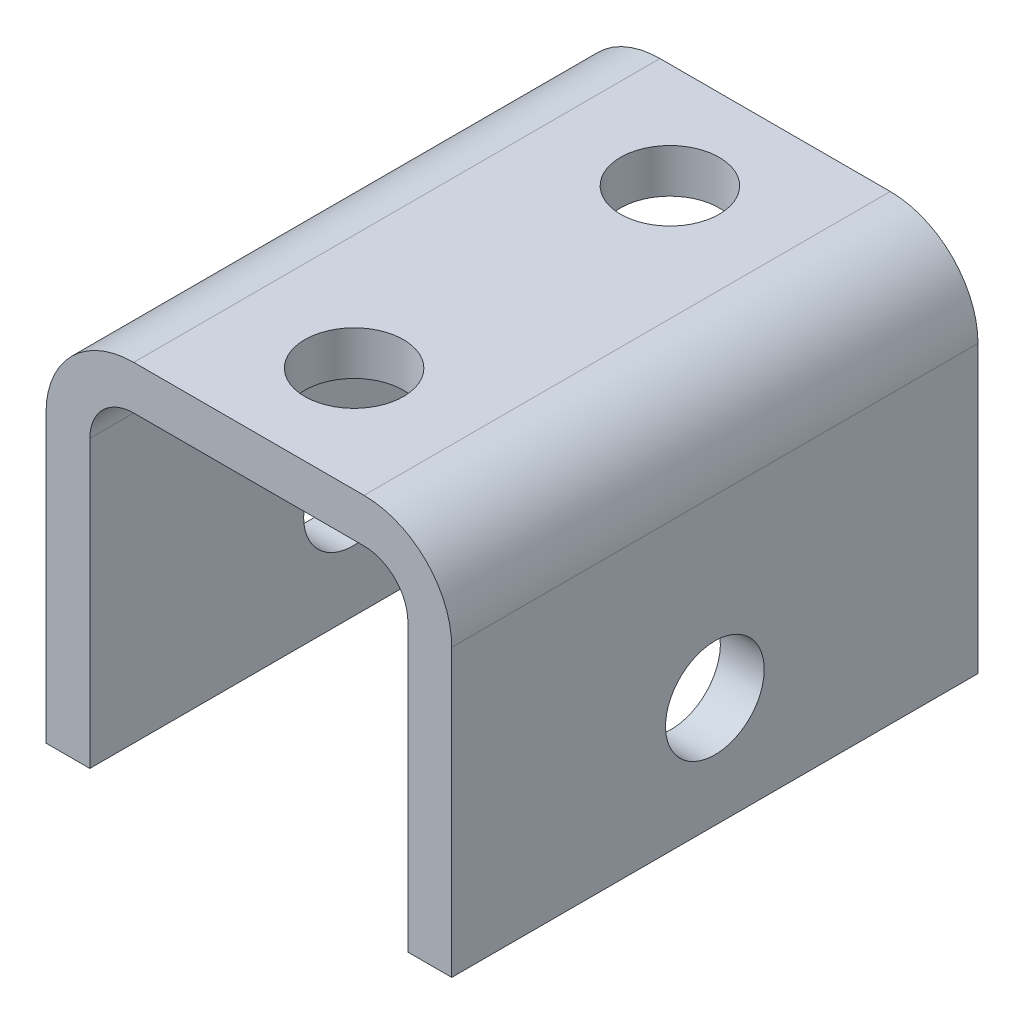
SolidWorks part; units mm, degrees
material "Plain Carbon Steel"
ref_plane "Front Plane" through (0, 0, 0) normal (0, 0, 1) x (1, 0, 0)
ref_plane "Top Plane" through (0, 0, 0) normal (0, 1, 0) x (1, 0, 0)
ref_plane "Right Plane" through (0, 0, 0) normal (1, 0, 0) x (0, 0, -1)
sketch "Sketch1" plane through (0, 0, 0) normal (0, 0, 1) x (1, 0, 0)
  line L0 (-23.0251, -12.7) -> (-23.0251, -54.102)
  line L1 (-16.6751, 0) -> (16.6751, 0)
  line L2 (-29.3751, -12.7) -> (-29.3751, -54.102)
  line L4 (29.3751, -12.7) -> (29.3751, -54.102)
  line L5 (-29.3751, 0) -> (29.3751, -54.102) construction
  line L6 (-29.3751, -54.102) -> (29.3751, 0) construction
  line L7 (-16.6751, -6.35) -> (16.6751, -6.35)
  line L8 (23.0251, -12.7) -> (23.0251, -54.102)
  line L9 (-29.3751, -54.102) -> (-23.0251, -54.102)
  line L10 (23.0251, -54.102) -> (29.3751, -54.102)
  arc A0 (16.6751, 0) -> (29.3751, -12.7) centre (16.6751, -12.7) cw
  arc A1 (-16.6751, 0) -> (-29.3751, -12.7) centre (-16.6751, -12.7) ccw
  arc A2 (-16.6751, -6.35) -> (-23.0251, -12.7) centre (-16.6751, -12.7) ccw
  arc A3 (16.6751, -6.35) -> (23.0251, -12.7) centre (16.6751, -12.7) cw
  point P4 (0, -27.051)
  dimension "D3" = 12.7
  dimension "D1" = 54.102
  dimension "D2" = 58.7502
  dimension "D4" = 29.3751
  dimension "D6" = 46.0502
  dimension "D5" = 6.35
extrude "Boss-Extrude1" add sketch "Sketch1" along normal mid plane 76.2
sketch "Sketch2" plane through (29.3751, 0, 0) normal (1, 0, 0) x (0, 0, -1)
  line L0 (0, 0) -> (0, -38.1) construction
  line L1 (-38.1, -54.102) -> (38.1, -54.102) construction
  circle A0 centre (0, -38.1) radius 7.1438
  dimension "D1" = 14.2875
  dimension "D2" = 38.1
  dimension "D3" = 16.002
extrude "Cut-Extrude1" cut sketch "Sketch2" against normal through all
sketch "Sketch3" plane through (0, 0, 0) normal (0, 1, 0) x (1, 0, 0)
  line L0 (0, 38.1) -> (0, 22.86) construction
  line L1 (16.6751, 38.1) -> (-16.6751, 38.1) construction
  line L2 (0, 22.86) -> (0, 7.62) construction
  line L3 (0, 7.62) -> (0, -7.62) construction
  line L4 (0, -7.62) -> (0, -22.86) construction
  line L5 (0, -22.86) -> (0, -38.1) construction
  line L6 (16.6751, -38.1) -> (-16.6751, -38.1) construction
  circle A0 centre (0, 22.86) radius 7.1438
  circle A1 centre (0, -22.86) radius 7.1438
  dimension "D1" = 14.2875
extrude "Cut-Extrude2" cut sketch "Sketch3" against normal through all
